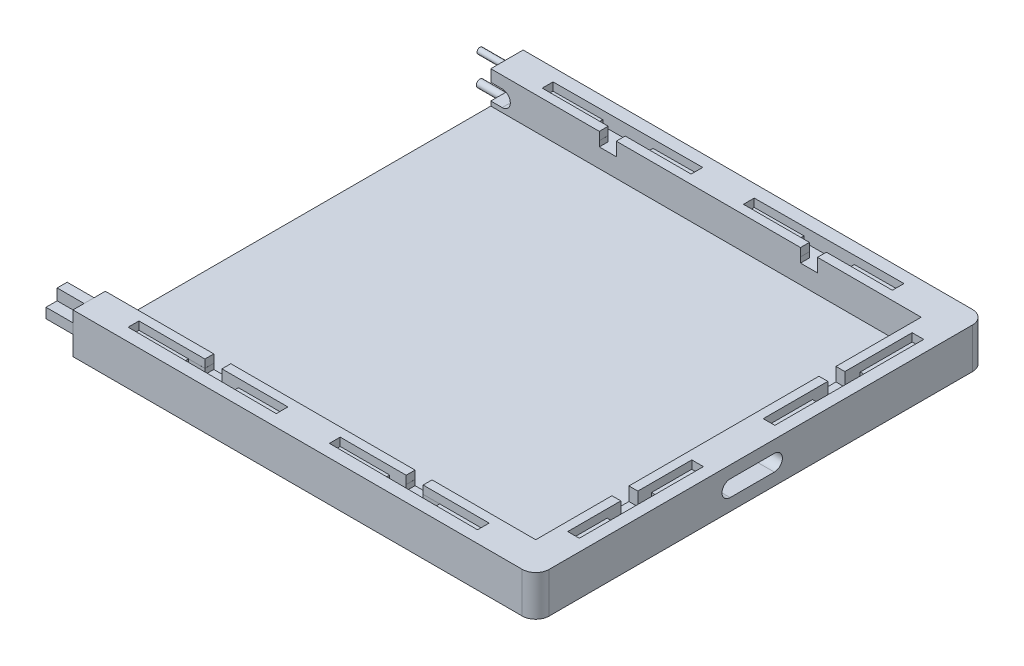
SolidWorks part; units mm, degrees
ref_plane "Front Plane" through (0, 0, 0) normal (0, 0, 1) x (1, 0, 0)
ref_plane "Top Plane" through (0, 0, 0) normal (0, 1, 0) x (1, 0, 0)
ref_plane "Right Plane" through (0, 0, 0) normal (1, 0, 0) x (0, 0, -1)
sketch "Sketch1" plane through (0, 0, 0) normal (0, 1, 0) x (1, 0, 0)
  line L0 (0, 152.7185) -> (0, -149.9342) construction
  line L1 (-90.768, 0) -> (299.0331, 0) construction
  line L2 (0, 71.4375) -> (159.54, 71.4375)
  line L3 (159.54, 71.4375) -> (159.54, -71.4375)
  line L4 (159.54, -71.4375) -> (0, -71.4375)
  line L5 (0, -71.4375) -> (0, 71.4375)
  dimension "D1" = 159.54
  dimension "D2" = 142.875
extrude "Boss-Extrude1" add sketch "Sketch1" along normal blind 3
sketch "Sketch3" plane through (0, 0, 0) normal (0, 1, 0) x (1, 0, 0)
  line L0 (0, 105.5814) -> (0, -111.8381) construction
  line L1 (-76.2859, 0) -> (270.0575, 0) construction
  line L2 (0, 71.4375) -> (0, 83.4375)
  line L3 (0, 83.4375) -> (171.54, 83.4375)
  line L4 (171.54, 83.4375) -> (171.54, -83.4375)
  line L5 (171.54, -83.4375) -> (0, -83.4375)
  line L6 (0, -83.4375) -> (0, -71.4375)
  line L7 (0, -71.4375) -> (159.54, -71.4375)
  line L8 (159.54, -71.4375) -> (159.54, 71.4375)
  line L9 (159.54, 71.4375) -> (0, 71.4375)
  dimension "D1" = 12
  dimension "D2" = 12
  dimension "D3" = 12
extrude "Boss-Extrude2" add sketch "Sketch3" along normal blind 15
sketch "Sketch4" plane through (0, 15, 0) normal (0, 1, 0) x (1, 0, 0)
  line L0 (46.52, 74.7375) -> (46.52, 71.4375)
  line L1 (70.97, 74.7375) -> (46.52, 74.7375)
  line L2 (70.9692, 79.0375) -> (70.97, 74.7375)
  line L3 (15.77, 78.7359) -> (70.9692, 79.0375)
  line L4 (15.77, 74.7359) -> (15.77, 78.7359)
  line L5 (40.22, 74.7359) -> (15.77, 74.7359)
  line L6 (40.22, 71.4375) -> (40.22, 74.7359)
  line L7 (46.52, 71.4375) -> (40.22, 71.4375)
  line L8 (121.11, 74.7375) -> (121.11, 71.4375)
  line L9 (145.56, 74.7375) -> (121.11, 74.7375)
  line L10 (145.5592, 79.0375) -> (145.56, 74.7375)
  line L11 (90.36, 78.7359) -> (145.5592, 79.0375)
  line L12 (90.36, 74.7359) -> (90.36, 78.7359)
  line L13 (114.81, 74.7359) -> (90.36, 74.7359)
  line L14 (114.81, 71.4375) -> (114.81, 74.7359)
  line L15 (121.11, 71.4375) -> (114.81, 71.4375)
  line L16 (0, 71.4375) -> (159.54, 71.4375) construction
  line L17 (0, 83.4375) -> (0, 71.4375) construction
  line L18 (159.54, 71.4375) -> (159.54, -71.4375) construction
  line L19 (-47.7177, 0) -> (229.914, 0) construction
  line L20 (145.56, -74.7375) -> (121.11, -74.7375)
  line L21 (145.5592, -79.0375) -> (145.56, -74.7375)
  line L22 (90.36, -78.7359) -> (145.5592, -79.0375)
  line L23 (90.36, -74.7359) -> (90.36, -78.7359)
  line L24 (114.81, -74.7359) -> (90.36, -74.7359)
  line L25 (114.81, -71.4375) -> (114.81, -74.7359)
  line L26 (121.11, -71.4375) -> (114.81, -71.4375)
  line L27 (121.11, -74.7375) -> (121.11, -71.4375)
  line L28 (70.97, -74.7375) -> (46.52, -74.7375)
  line L29 (70.9692, -79.0375) -> (70.97, -74.7375)
  line L30 (15.77, -78.7359) -> (70.9692, -79.0375)
  line L31 (15.77, -74.7359) -> (15.77, -78.7359)
  line L32 (40.22, -74.7359) -> (15.77, -74.7359)
  line L33 (40.22, -71.4375) -> (40.22, -74.7359)
  line L34 (46.52, -71.4375) -> (40.22, -71.4375)
  line L35 (46.52, -74.7375) -> (46.52, -71.4375)
  line L36 (0, -71.4375) -> (0, -83.4375) construction
  line L37 (159.54, -71.4375) -> (159.54, 71.4375) construction
  line L38 (0, 10.7675) -> (159.54, 10.7675) construction
  line L39 (0, 71.4375) -> (0, -71.4375) construction
  line L40 (159.54, -36.8875) -> (162.84, -36.8875)
  line L49 (159.54, 39.8375) -> (162.84, 39.8375)
  line L50 (162.84, 39.8375) -> (162.84, 64.7884)
  line L51 (162.84, 64.7884) -> (167.14, 64.7884)
  line L52 (167.14, 64.7884) -> (167.14, 9.5884)
  line L53 (167.14, 9.5884) -> (162.84, 9.5884)
  line L54 (162.84, 33.5375) -> (162.84, 9.5884)
  line L55 (159.54, 33.5375) -> (162.84, 33.5375)
  line L56 (159.54, 39.8375) -> (159.54, 33.5375)
  line L57 (162.84, -36.8875) -> (162.84, -16.8875)
  line L58 (162.84, -16.8875) -> (167.14, -16.8875)
  line L59 (167.14, -16.8875) -> (167.14, -62.8875)
  line L60 (167.14, -62.8875) -> (162.84, -62.8875)
  line L61 (162.84, -43.1875) -> (162.84, -62.8875)
  line L62 (159.54, -43.1875) -> (162.84, -43.1875)
  line L63 (159.54, -36.8875) -> (159.54, -43.1875)
  line L64 (0, -71.4375) -> (159.54, -71.4375) construction
  dimension "D1" = 6.3
  dimension "D2" = 3.3
  dimension "D3" = 4.3
  dimension "D4" = 55.2
  dimension "D5" = 6.3
  dimension "D6" = 3.3
  dimension "D7" = 4.3
  dimension "D8" = 55.2
  dimension "D9" = 0
  dimension "D10" = 0
  dimension "D11" = 40.22
  dimension "D12" = 38.43
  dimension "D13" = 55.1992
  dimension "D14" = 40.22
  dimension "D15" = 38.43
  dimension "D16" = 0
  dimension "D17" = 31.6
  dimension "D18" = 6.3
  dimension "D19" = 55.2
  dimension "D20" = 28.25
  dimension "D21" = 6.3
  dimension "D22" = 46
  dimension "D23" = 20
  dimension "D24" = 3.3
extrude "Cut-Extrude1" cut sketch "Sketch4" against normal blind 3
sketch "Sketch5" plane through (0, 12, 0) normal (0, 1, 0) x (1, 0, 0)
  line L0 (40.2268, -74.7375) -> (28.0018, -74.7375) construction
  line L1 (46.5257, -74.7375) -> (58.7524, -74.7375) construction
  line L2 (40.2268, -71.4375) -> (40.2268, -74.7375)
  line L3 (40.2268, -74.7375) -> (34.1143, -74.7375)
  line L4 (34.1143, -74.7375) -> (34.1143, -78.8361)
  line L5 (34.1143, -78.8361) -> (52.639, -78.9373)
  line L6 (52.639, -78.9373) -> (52.639, -74.7375)
  line L7 (46.5257, -71.4375) -> (40.2268, -71.4375)
  line L8 (46.5257, -71.4375) -> (46.5257, -74.7375)
  line L9 (46.5257, -74.7375) -> (52.639, -74.7375)
  line L10 (114.8174, -74.7359) -> (102.5924, -74.7359) construction
  line L11 (121.1171, -74.7359) -> (133.3421, -74.7359) construction
  line L12 (114.8174, -74.7359) -> (108.7049, -74.7359)
  line L13 (108.7049, -74.7359) -> (108.7049, -78.8361)
  line L14 (108.7049, -78.8361) -> (127.2296, -78.9373)
  line L15 (127.2296, -78.9373) -> (127.2296, -74.7359)
  line L16 (127.2296, -74.7359) -> (121.1171, -74.7359)
  line L17 (121.1171, -74.7359) -> (121.1171, -71.4375)
  line L18 (121.1171, -71.4375) -> (114.8174, -71.4375)
  line L19 (114.8174, -71.4375) -> (114.8174, -74.7359)
  line L20 (0, -71.4375) -> (159.54, -71.4375) construction
  line L21 (162.84, -36.8875) -> (159.54, -36.8875) construction
  line L22 (15.77, -78.7359) -> (70.9692, -79.0375) construction
  line L23 (70.97, -74.7375) -> (46.52, -74.7375) construction
  line L24 (43.3767, -68.4649) -> (43.3767, -82.099) construction
  line L25 (159.54, -43.1875) -> (162.84, -43.1875) construction
  line L26 (90.36, -78.7359) -> (145.5592, -79.0375) construction
  line L27 (114.81, -74.7359) -> (90.36, -74.7359) construction
  line L28 (117.9672, -70.6619) -> (117.9672, -81.6393) construction
  line L29 (-14.3619, 0) -> (206.3964, 0) construction
  line L30 (114.8174, 71.4375) -> (114.8174, 74.7359)
  line L31 (121.1171, 71.4375) -> (114.8174, 71.4375)
  line L32 (121.1171, 74.7359) -> (121.1171, 71.4375)
  line L33 (127.2296, 74.7359) -> (121.1171, 74.7359)
  line L34 (127.2296, 78.9373) -> (127.2296, 74.7359)
  line L35 (108.7049, 78.8361) -> (127.2296, 78.9373)
  line L36 (108.7049, 74.7359) -> (108.7049, 78.8361)
  line L37 (114.8174, 74.7359) -> (108.7049, 74.7359)
  line L38 (46.5257, 71.4375) -> (40.2268, 71.4375)
  line L39 (46.5257, 71.4375) -> (46.5257, 74.7375)
  line L40 (46.5257, 74.7375) -> (52.639, 74.7375)
  line L41 (52.639, 78.9373) -> (52.639, 74.7375)
  line L42 (34.1143, 78.8361) -> (52.639, 78.9373)
  line L43 (34.1143, 74.7375) -> (34.1143, 78.8361)
  line L44 (40.2268, 74.7375) -> (34.1143, 74.7375)
  line L45 (40.2268, 71.4375) -> (40.2268, 74.7375)
  line L48 (159.54, -71.4375) -> (159.54, 71.4375) construction
  line L49 (159.54, 33.5375) -> (162.84, 33.5375) construction
  line L56 (162.84, 39.8375) -> (159.54, 39.8375) construction
  line L59 (157.6179, 36.6875) -> (170.3436, 36.6875) construction
  line L66 (96.0172, 13.3148) -> (96.0172, -25.9889) construction
  line L67 (162.84, -31.8125) -> (167.14, -31.8125)
  line L68 (162.84, -36.8875) -> (162.84, -31.8125)
  line L69 (159.54, -36.8875) -> (162.84, -36.8875)
  line L70 (159.54, -43.1875) -> (159.54, -36.8875)
  line L71 (162.84, -43.1875) -> (159.54, -43.1875)
  line L72 (162.84, -48.2625) -> (162.84, -43.1875)
  line L73 (167.14, -48.2625) -> (162.84, -48.2625)
  line L74 (167.14, -31.8125) -> (167.14, -48.2625)
  line L75 (159.54, 39.8375) -> (162.84, 39.8375)
  line L76 (162.84, 39.8375) -> (162.84, 45.5248)
  line L77 (162.84, 45.5248) -> (167.14, 45.5248)
  line L78 (167.14, 45.5248) -> (167.14, 27.8502)
  line L79 (167.14, 27.8502) -> (162.84, 27.8502)
  line L80 (162.84, 27.8502) -> (162.84, 33.5375)
  line L81 (159.54, 33.5375) -> (162.84, 33.5375)
  line L82 (159.54, 39.8375) -> (159.54, 33.5375)
  line L83 (167.14, 9.5884) -> (167.14, 64.7884) construction
  line L84 (162.84, 64.7884) -> (162.84, 39.8375) construction
  line L85 (167.14, -62.8875) -> (167.14, -16.8875) construction
  line L94 (158.2993, -40.0375) -> (170.1106, -40.0375) construction
extrude "Cut-Extrude2" cut sketch "Sketch5" against normal blind 2
sketch "Sketch6" plane through (171.54, 0, 0) normal (1, 0, 0) x (0, 0, -1)
  line L0 (-11.3875, 10.5) -> (4.9925, 10.5)
  line L1 (-11.3875, 4.5) -> (4.9925, 4.5)
  line L2 (-14.3875, 5.5661) -> (-14.3875, 9.4339) construction
  line L5 (-83.4375, 7.5) -> (83.4375, 7.5) construction
  line L6 (-83.4375, 15) -> (-83.4375, 0) construction
  line L7 (83.4375, 15) -> (83.4375, 0) construction
  arc A0 (-11.3875, 4.5) -> (-11.3875, 10.5) centre (-11.3875, 7.5) cw
  arc A1 (4.9925, 10.5) -> (4.9925, 4.5) centre (4.9925, 7.5) cw
  point P6 (-11.3875, 10.5)
  point P9 (-14.3875, 7.5)
  dimension "D2" = 3
  dimension "D1" = 16.38
  dimension "D3" = 69.05
extrude "Cut-Extrude3" cut sketch "Sketch6" against normal blind 12
sketch "Sketch7" plane through (0, 0, -83.4375) normal (0, 0, -1) x (-1, 0, 0)
  line L0 (31.7354, 7.6343) -> (-33.2248, 7.6343) construction
  line L1 (-4.24, 10.6343) -> (12.14, 10.6343)
  line L2 (-4.24, 4.6343) -> (12.14, 4.6343)
  line L3 (-7.24, 4.7002) -> (-7.24, 10.5684) construction
  line L4 (0, 15) -> (0, 0) construction
  line L5 (-171.54, 0) -> (0, 0) construction
  arc A0 (-4.24, 4.6343) -> (-4.24, 10.6343) centre (-4.24, 7.6343) cw
  arc A1 (12.14, 10.6343) -> (12.14, 4.6343) centre (12.14, 7.6343) cw
  point P8 (-4.24, 10.6343)
  point P11 (-7.24, 7.6343)
  dimension "D2" = 3
  dimension "D1" = 16.38
  dimension "D3" = 7.24
  dimension "D4" = 7.6343
extrude "Cut-Extrude4" cut sketch "Sketch7" against normal blind 12
sketch "Sketch8" plane through (0, 0, 0) normal (-1, 0, 0) x (0, 0, 1)
  line L0 (-77.4375, 4.6343) -> (-77.4375, 0.0234) construction
  line L1 (-71.4375, 4.6343) -> (-83.4375, 4.6343) construction
  line L2 (-83.4375, 12.8171) -> (-71.4375, 12.8171) construction
  line L3 (-83.4375, 15) -> (-83.4375, 10.6343) construction
  line L4 (-71.4375, 15) -> (-71.4375, 10.6343) construction
  circle A0 centre (-77.4375, 12.8171) radius 1.1
  circle A1 centre (-77.4375, 2.3288) radius 1.35
  dimension "D1" = 2.2
  dimension "D2" = 2.7
extrude "Boss-Extrude3" add sketch "Sketch8" along normal blind 10
sketch "Sketch9" plane through (0, 0, 0) normal (-1, 0, 0) x (0, 0, 1)
  line L2 (71.4375, 9) -> (83.4375, 9) construction
  line L3 (71.4375, 15) -> (71.4375, 3) construction
  line L4 (83.4375, 15) -> (83.4375, 0) construction
  line L5 (71.4375, 3) -> (83.4375, 3) construction
  line L6 (77.4375, 15) -> (77.4375, 3) construction
  line L7 (71.4375, 15) -> (83.4375, 15) construction
  line L8 (83.4212, 3.0166) -> (83.4212, 14.9834) construction
  line L9 (83.4212, 14.9834) -> (71.4538, 14.9834) construction
  line L10 (71.4538, 14.9834) -> (71.455, 3.0166) construction
  line L11 (71.455, 3.0166) -> (83.4212, 3.0166) construction
  line L12 (83.4212, 3.0166) -> (71.4538, 14.9834) construction
  line L13 (71.4538, 14.9834) -> (83.4212, 14.9834) construction
  line L14 (83.4212, 14.9834) -> (71.455, 3.0166) construction
  line L15 (77.4375, 15.1883) -> (77.4375, 3.0166) construction
  line L16 (71.4544, 9) -> (83.4994, 9) construction
  line L17 (75.5875, 14.9834) -> (79.2875, 14.9834)
  line L18 (83.4212, 7.15) -> (83.4212, 10.85)
  line L19 (79.2875, 3.0166) -> (75.5875, 3.0166)
  line L20 (71.4546, 7.15) -> (71.4542, 10.85)
  line L21 (75.5875, 14.9834) -> (75.5875, 10.85)
  line L22 (75.5875, 10.85) -> (71.4542, 10.85)
  line L23 (71.4546, 7.15) -> (75.5875, 7.15)
  line L24 (75.5875, 7.15) -> (75.5875, 3.0166)
  line L25 (79.2875, 3.0166) -> (79.2875, 7.15)
  line L26 (79.2875, 7.15) -> (83.4212, 7.15)
  line L27 (83.4212, 10.85) -> (79.2875, 10.85)
  line L28 (79.2875, 10.85) -> (79.2875, 14.9834)
  line L29 (77.4375, 9) -> (77.4375, 14.9834) construction
  line L30 (83.4212, 9) -> (71.4544, 9) construction
  point P26 (77.4375, 14.9834)
  point P30 (83.4212, 9)
  point P33 (77.4375, 3.0166)
  point P36 (71.4544, 9)
  point P43 (77.4375, 9)
  dimension "D1" = 3.7
  dimension "D2" = 3.7
  dimension "D3" = 3.7
  dimension "D4" = 3.7
  dimension "D5" = 0
extrude "Boss-Extrude5" add sketch "Sketch9" along normal blind 10
fillet "Fillet3" radius 5 1 edges at (171.54, 7.5, 83.4375)
fillet "Fillet4" radius 5 1 edges at (171.54, 7.5, -83.4375)
